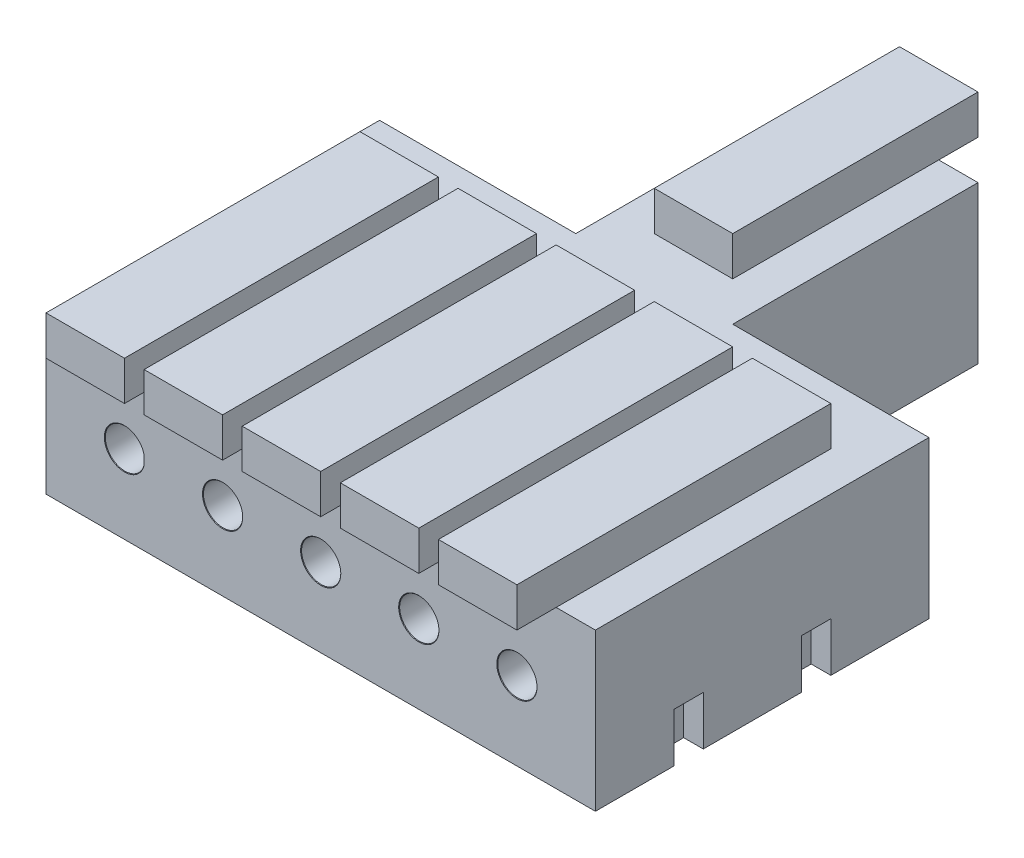
SolidWorks part; units mm, degrees
material "ABS"
ref_plane "Front Plane" through (0, 0, 0) normal (0, 0, 1) x (1, 0, 0)
ref_plane "Top Plane" through (0, 0, 0) normal (0, 1, 0) x (1, 0, 0)
ref_plane "Right Plane" through (0, 0, 0) normal (1, 0, 0) x (0, 0, -1)
sketch "Sketch1" plane through (0, 0, 0) normal (0, 1, 0) x (1, 0, 0)
  line L1 (0, 0) -> (8, 0)
  line L2 (0, 0) -> (0, 17)
  line L3 (0, 17) -> (8, 17)
  line L4 (8, 0) -> (8, 17)
  dimension "D1" = 8
  dimension "D2" = 17
extrude "connector_body" add sketch "Sketch1" along normal blind 8
sketch "Sketch2" plane through (0, 0, 0) normal (0, 0, -1) x (-1, 0, 0)
  line L0 (0, 8) -> (0, 0) construction
  line L1 (-8, 8) -> (0, 8) construction
  point P0 (-4, 4)
  dimension "D1" = 4
  dimension "D2" = 4
hole_wizard "cable_hole" positions "Sketch2" profile "Sketch3" hole size "Ø2.0" standard "DIN"
sketch "Sketch3" plane through (4, 4, 0) normal (1, 0, 0) x (0, -1, 0)
  line L0 (0, 0) -> (0, 10.6009)
  line L1 (0, 10.6009) -> (1, 10)
  line L2 (1, 10) -> (1, 0.025)
  line L3 (1, 0.025) -> (1.025, 0)
  line L5 (1.025, 0) -> (0, 0)
  line L6 (-1, 0.025) -> (-1.025, 0) construction
  line L10 (0, 10.6009) -> (-1, 10) construction
  line L11 (0, -6.35) -> (0, 107.95) construction
  dimension "Hole Dia." = 2
  dimension "Hole Depth" = 10
  dimension "Near C'Sink Dia." = 2.05
  dimension "Near C'Sink Angle" = 90
  dimension "Drill Angle" = 118
sketch "Sketch4" plane through (0, 8, 0) normal (0, 1, 0) x (1, 0, 0)
  line L0 (8, 0) -> (8, 17) construction
  line L1 (2, 14) -> (6, 14)
  line L2 (2, 14) -> (2, -2)
  line L3 (2, -2) -> (6, -2)
  line L4 (6, 14) -> (6, -2)
  line L6 (8, 17) -> (0, 17) construction
  dimension "D1" = 4
  dimension "D2" = 2
  dimension "D3" = 3
  dimension "D4" = 16
extrude "clamp" add sketch "Sketch4" along normal blind 2
pattern_linear "connector_pattern" count 5 spacing 5 along (1, 0, 0) of "connector_body", "cable_hole", "clamp"
sketch "Sketch5" plane through (0, 8, 0) normal (0, 1, 0) x (1, 0, 0)
  line L0 (28, 17) -> (0, 17) construction
  line L1 (10, 17) -> (18, 17)
  line L2 (10, 17) -> (10, 29.5)
  line L3 (10, 29.5) -> (18, 29.5)
  line L4 (18, 17) -> (18, 29.5)
  line L5 (0, 17) -> (0, 0) construction
  dimension "D1" = 8
  dimension "D2" = 10
  dimension "D3" = 12.5
extrude "single_body" add sketch "Sketch5" against normal up to vertex (8 mm away)
sketch "Sketch6" plane through (0, 0, 0) normal (-1, 0, 0) x (0, 0, 1)
  line L0 (-17, 0) -> (0, 0) construction
  line L1 (-12, 0) -> (-10.5, 0)
  line L2 (-12, 0) -> (-12, 2.5004)
  line L3 (-12, 2.5004) -> (-10.5, 2.5004)
  line L4 (-10.5, 0) -> (-10.5, 2.5004)
  line L5 (-17, 0) -> (-17, 8) construction
  line L6 (-5.5, 0) -> (-4, 0)
  line L7 (-5.5, 0) -> (-5.5, 2.5004)
  line L8 (-5.5, 2.5004) -> (-4, 2.5004)
  line L9 (-4, 0) -> (-4, 2.5004)
  point P12 (-4.75, 0)
  dimension "D1" = 5
  dimension "D2" = 1.5
  dimension "D3" = 1.5
  dimension "D4" = 2.5004
  dimension "D5" = 5
extrude "chaining_nobs" add sketch "Sketch6" along normal blind 1
sketch "Sketch7" plane through (0, 0, 0) normal (0, -1, 0) x (1, 0, 0)
  line L1 (28, -4) -> (27, -4)
  line L2 (28, -4) -> (28, -5.5)
  line L3 (28, -5.5) -> (27, -5.5)
  line L4 (27, -4) -> (27, -5.5)
  line L5 (-1, -10.5) -> (0, -10.5) construction
  line L6 (27, -12) -> (28, -12)
  line L7 (27, -12) -> (27, -10.5)
  line L8 (27, -10.5) -> (28, -10.5)
  line L9 (28, -12) -> (28, -10.5)
  line L10 (28, 0) -> (28, -17) construction
  line L11 (-1, -5.5) -> (0, -5.5) construction
  dimension "D1" = 1
  dimension "D2" = 1.5
sketch "Sketch8" plane through (0, 8, 0) normal (0, 1, 0) x (1, 0, 0)
  line L0 (10, 29.5) -> (10, 17) construction
  line L1 (12, 19) -> (16, 19)
  line L2 (12, 19) -> (12, 31.5)
  line L3 (12, 31.5) -> (16, 31.5)
  line L4 (16, 19) -> (16, 31.5)
  line L5 (28, 17) -> (18, 17) construction
  line L6 (18, 29.5) -> (10, 29.5) construction
  dimension "D1" = 4
  dimension "D2" = 2
  dimension "D3" = 2
  dimension "D4" = 2
extrude "chaining_nobs_cutout" cut sketch "Sketch7" against normal up to vertex (2.5004 mm away)
extrude "single_body_clamp" add sketch "Sketch8" along normal up to vertex (2 mm away)
sketch "Sketch9" plane through (0, 0, 0) normal (0, -1, 0) x (1, 0, 0)
  line L1 (10, -29.5) -> (10, -17) construction
  line L2 (18, -29.5) -> (10, -29.5) construction
  circle A0 centre (8, -19) radius 2.25
  circle A1 centre (8, -19) radius 1.5
  circle A2 centre (20, -19) radius 1.5
  circle A3 centre (20, -19) radius 2.25
  dimension "D2" = 2
  dimension "D3" = 4.5
  dimension "D4" = 3
  dimension "D1" = 12
  dimension "D5" = 10.5
extrude "mounting_rings" add sketch "Sketch9" against normal blind 2
